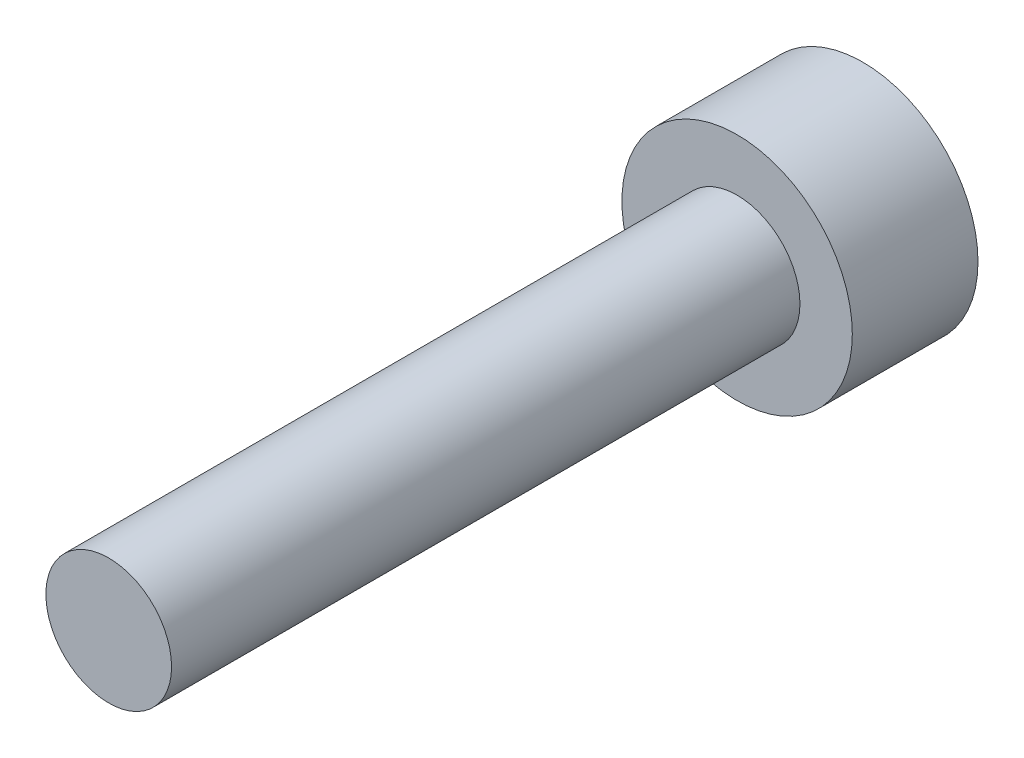
SolidWorks part; units mm, degrees
ref_plane "Plano frontal" through (0, 0, 0) normal (0, 0, 1) x (1, 0, 0)
ref_plane "Plano superior" through (0, 0, 0) normal (0, 1, 0) x (1, 0, 0)
ref_plane "Plano direito" through (0, 0, 0) normal (1, 0, 0) x (0, 0, -1)
sketch "Esboço1" plane through (0, 0, 0) normal (0, 0, 1) x (1, 0, 0)
  circle A0 centre (0, 0) radius 2.75
  dimension "D1" = 5.5
extrude "Ressalto-extrusão1" add sketch "Esboço1" along normal blind 3
sketch "Esboço2" plane through (0, 0, 3) normal (0, 0, 1) x (1, 0, 0)
  circle A0 centre (0, 0) radius 1.5
  dimension "D1" = 3
extrude "Ressalto-extrusão2" add sketch "Esboço2" along normal blind 15
